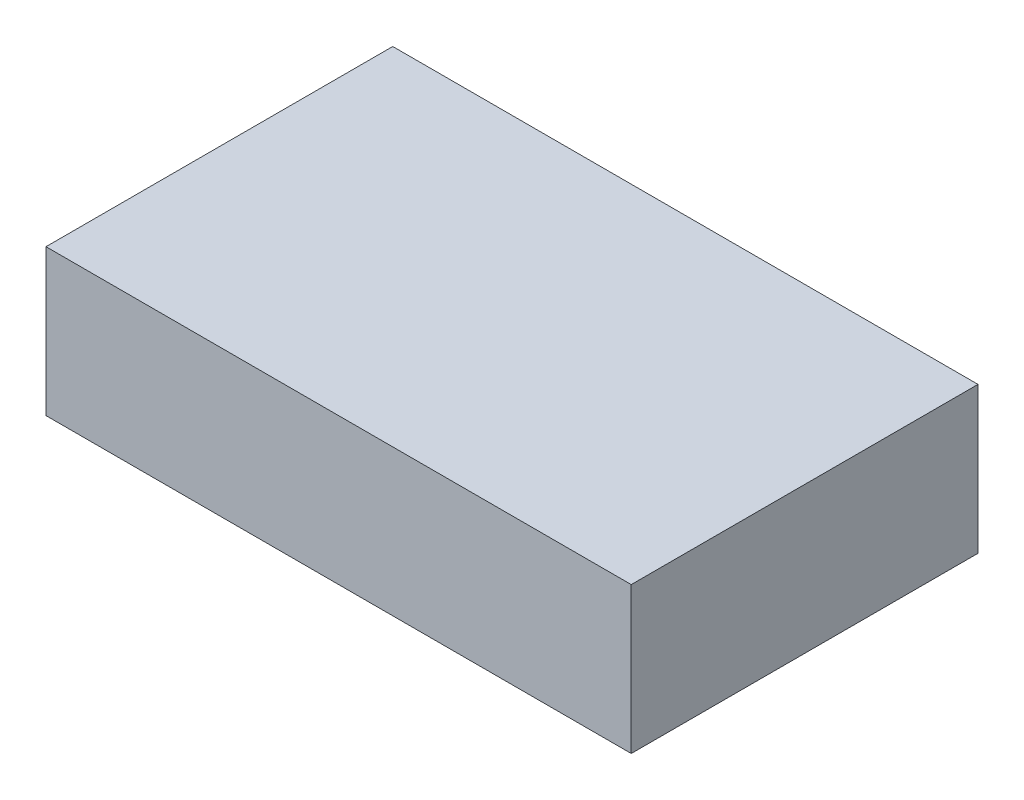
SolidWorks part; units mm, degrees
ref_plane "Front Plane" through (0, 0, 0) normal (0, 0, 1) x (1, 0, 0)
ref_plane "Top Plane" through (0, 0, 0) normal (0, 1, 0) x (1, 0, 0)
ref_plane "Right Plane" through (0, 0, 0) normal (1, 0, 0) x (0, 0, -1)
sketch "Sketch1" plane through (0, 0, 0) normal (0, 1, 0) x (1, 0, 0)
  line L1 (0, 0) -> (40, 0)
  line L2 (0, 0) -> (0, 23.7)
  line L3 (0, 23.7) -> (40, 23.7)
  line L4 (40, 0) -> (40, 23.7)
extrude "Boss-Extrude1" add sketch "Sketch1" against normal blind 10
